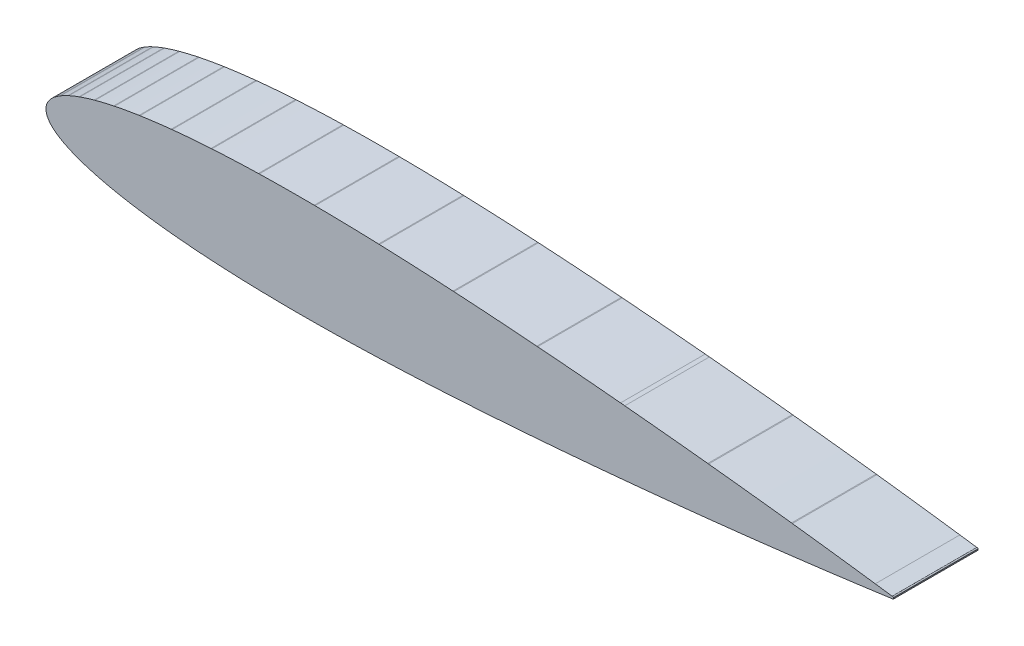
SolidWorks part; units mm, degrees
ref_plane "Front Plane" through (0, 0, 0) normal (0, 0, 1) x (1, 0, 0)
ref_plane "Top Plane" through (0, 0, 0) normal (0, 1, 0) x (1, 0, 0)
ref_plane "Right Plane" through (0, 0, 0) normal (1, 0, 0) x (0, 0, -1)
sketch "Model" plane through (0, 0, 0) normal (0, 0, 1) x (1, 0, 0)
  line L0 (0.8374, 4.1947) -> (0.812, 4.2382)
  line L1 (0.8628, 4.1583) -> (0.8374, 4.1947)
  line L2 (0.8882, 4.1265) -> (0.8628, 4.1583)
  line L3 (0.9136, 4.098) -> (0.8882, 4.1265)
  line L4 (0.939, 4.0719) -> (0.9136, 4.098)
  line L5 (0.9644, 4.0477) -> (0.939, 4.0719)
  line L6 (0.9898, 4.0252) -> (0.9644, 4.0477)
  line L7 (1.0152, 4.004) -> (0.9898, 4.0252)
  line L8 (1.193, 3.8809) -> (1.1676, 3.8965)
  line L9 (1.447, 3.7489) -> (1.4216, 3.7606)
  line L10 (1.7772, 3.6169) -> (1.7518, 3.6259)
  line L11 (2.2344, 3.4756) -> (2.209, 3.4825)
  line L12 (2.8186, 3.3374) -> (2.7932, 3.3427)
  line L13 (3.5806, 3.2027) -> (3.5552, 3.2066)
  line L14 (4.5458, 3.0817) -> (4.5204, 3.0843)
  line L15 (5.7396, 2.9854) -> (5.7142, 2.987)
  line L16 (7.162, 2.9264) -> (7.1366, 2.927)
  line L17 (8.8384, 2.9141) -> (8.813, 2.9139)
  line L18 (10.7688, 2.9572) -> (10.7434, 2.9563)
  line L19 (13.004, 3.0641) -> (12.9786, 3.0626)
  line L20 (15.5186, 3.2388) -> (15.4932, 3.2368)
  line L21 (20.6494, 3.7231) -> (20.624, 3.7204)
  line L22 (23.164, 4.0127) -> (23.1386, 4.0096)
  line L23 (0.8374, 4.6787) -> (0.812, 4.6352)
  line L24 (0.8628, 4.7151) -> (0.8374, 4.6787)
  line L25 (0.8882, 4.7469) -> (0.8628, 4.7151)
  line L26 (0.9136, 4.7755) -> (0.8882, 4.7469)
  line L27 (0.939, 4.8016) -> (0.9136, 4.7755)
  line L28 (0.9644, 4.8257) -> (0.939, 4.8016)
  line L29 (0.9898, 4.8483) -> (0.9644, 4.8257)
  line L30 (1.0152, 4.8695) -> (0.9898, 4.8483)
  line L31 (1.193, 4.9925) -> (1.1676, 4.977)
  line L32 (1.447, 5.1245) -> (1.4216, 5.1128)
  line L33 (1.7772, 5.2566) -> (1.7518, 5.2475)
  line L34 (2.2344, 5.3979) -> (2.209, 5.3909)
  line L35 (2.8186, 5.536) -> (2.7932, 5.5308)
  line L36 (3.5806, 5.6707) -> (3.5552, 5.6669)
  line L37 (4.5458, 5.7918) -> (4.5204, 5.7892)
  line L38 (5.7396, 5.888) -> (5.7142, 5.8865)
  line L39 (7.162, 5.9471) -> (7.1366, 5.9464)
  line L40 (8.8384, 5.9593) -> (8.813, 5.9595)
  line L41 (10.7688, 5.9162) -> (10.7434, 5.9171)
  line L42 (13.004, 5.8093) -> (12.9786, 5.8108)
  line L43 (15.5186, 5.6347) -> (15.4932, 5.6367)
  line L44 (20.6494, 5.1503) -> (20.624, 5.1531)
  line L45 (23.164, 4.8608) -> (23.1386, 4.8639)
  line L46 (26.1612, 4.4047) -> (25.6532, 4.3343)
  line L47 (26.1612, 4.4687) -> (25.6532, 4.5391)
  line L48 (18.1348, 5.4064) -> (18.0078, 5.4185)
  line L49 (18.1348, 3.467) -> (18.0078, 3.455)
  arc A0 (0.7612, 4.4367) -> (0.812, 4.2382) centre (1.1744, 4.4367) ccw
  arc A1 (26.1612, 4.4047) -> (26.1893, 4.4367) centre (26.1753, 4.4207) ccw
  arc A2 (1.0152, 4.004) -> (1.1676, 3.8965) centre (1.9774, 5.206) ccw
  arc A3 (1.193, 3.8809) -> (1.4216, 3.7606) centre (2.4761, 6.041) ccw
  arc A4 (1.447, 3.7489) -> (1.7518, 3.6259) centre (3.1067, 7.424) ccw
  arc A5 (1.7772, 3.6169) -> (2.209, 3.4825) centre (3.8908, 9.6488) ccw
  arc A6 (2.2344, 3.4756) -> (2.7932, 3.3427) centre (4.7676, 12.8852) ccw
  arc A7 (2.8186, 3.3374) -> (3.5552, 3.2066) centre (5.6968, 17.4001) ccw
  arc A8 (3.5806, 3.2027) -> (4.5204, 3.0843) centre (6.6196, 23.5317) ccw
  arc A9 (4.5458, 3.0817) -> (5.7142, 2.987) centre (7.4443, 31.5889) ccw
  arc A10 (5.7396, 2.9854) -> (7.1366, 2.927) centre (8.0642, 41.8615) ccw
  arc A11 (7.162, 2.9264) -> (8.813, 2.9139) centre (8.3826, 55.2927) ccw
  arc A12 (8.8384, 2.9141) -> (10.7434, 2.9563) centre (8.2345, 73.2039) ccw
  arc A13 (10.7688, 2.9572) -> (12.9786, 3.0626) centre (7.3567, 97.7261) ccw
  arc A14 (13.004, 3.0641) -> (15.4932, 3.2368) centre (5.4178, 130.4697) ccw
  arc A15 (15.5186, 3.2388) -> (18.0078, 3.455) centre (2.5873, 166.5357) ccw
  arc A16 (18.1348, 3.467) -> (20.624, 3.7204) centre (0.1449, 192.5771) ccw
  arc A17 (20.6494, 3.7231) -> (23.1386, 4.0096) centre (0.0317, 193.84) ccw
  arc A18 (23.164, 4.0127) -> (25.6532, 4.3343) centre (2.5402, 173.4111) ccw
  arc A19 (0.812, 4.6352) -> (0.7612, 4.4367) centre (1.1744, 4.4367) ccw
  arc A20 (26.1893, 4.4367) -> (26.1612, 4.4687) centre (26.1753, 4.4527) ccw
  arc A21 (1.1676, 4.977) -> (1.0152, 4.8695) centre (1.9774, 3.6675) ccw
  arc A22 (1.4216, 5.1128) -> (1.193, 4.9925) centre (2.4761, 2.8324) ccw
  arc A23 (1.7518, 5.2475) -> (1.447, 5.1245) centre (3.1067, 1.4494) ccw
  arc A24 (2.209, 5.3909) -> (1.7772, 5.2566) centre (3.8908, -0.7753) ccw
  arc A25 (2.7932, 5.5308) -> (2.2344, 5.3979) centre (4.7676, -4.0118) ccw
  arc A26 (3.5552, 5.6669) -> (2.8186, 5.536) centre (5.6968, -8.5266) ccw
  arc A27 (4.5204, 5.7892) -> (3.5806, 5.6707) centre (6.6196, -14.6583) ccw
  arc A28 (5.7142, 5.8865) -> (4.5458, 5.7918) centre (7.4443, -22.7154) ccw
  arc A29 (7.1366, 5.9464) -> (5.7396, 5.888) centre (8.0642, -32.9881) ccw
  arc A30 (8.813, 5.9595) -> (7.162, 5.9471) centre (8.3826, -46.4193) ccw
  arc A31 (10.7434, 5.9171) -> (8.8384, 5.9593) centre (8.2345, -64.3304) ccw
  arc A32 (12.9786, 5.8108) -> (10.7688, 5.9162) centre (7.3567, -88.8526) ccw
  arc A33 (15.4932, 5.6367) -> (13.004, 5.8093) centre (5.4178, -121.5962) ccw
  arc A34 (18.0078, 5.4185) -> (15.5186, 5.6347) centre (2.5873, -157.6623) ccw
  arc A35 (20.624, 5.1531) -> (18.1348, 5.4064) centre (0.1449, -183.7037) ccw
  arc A36 (23.1386, 4.8639) -> (20.6494, 5.1503) centre (0.0317, -184.9666) ccw
  arc A37 (25.6532, 4.5391) -> (23.164, 4.8608) centre (2.5402, -164.5376) ccw
extrude "Boss-Extrude1" add sketch "Model" along normal blind 2.54
